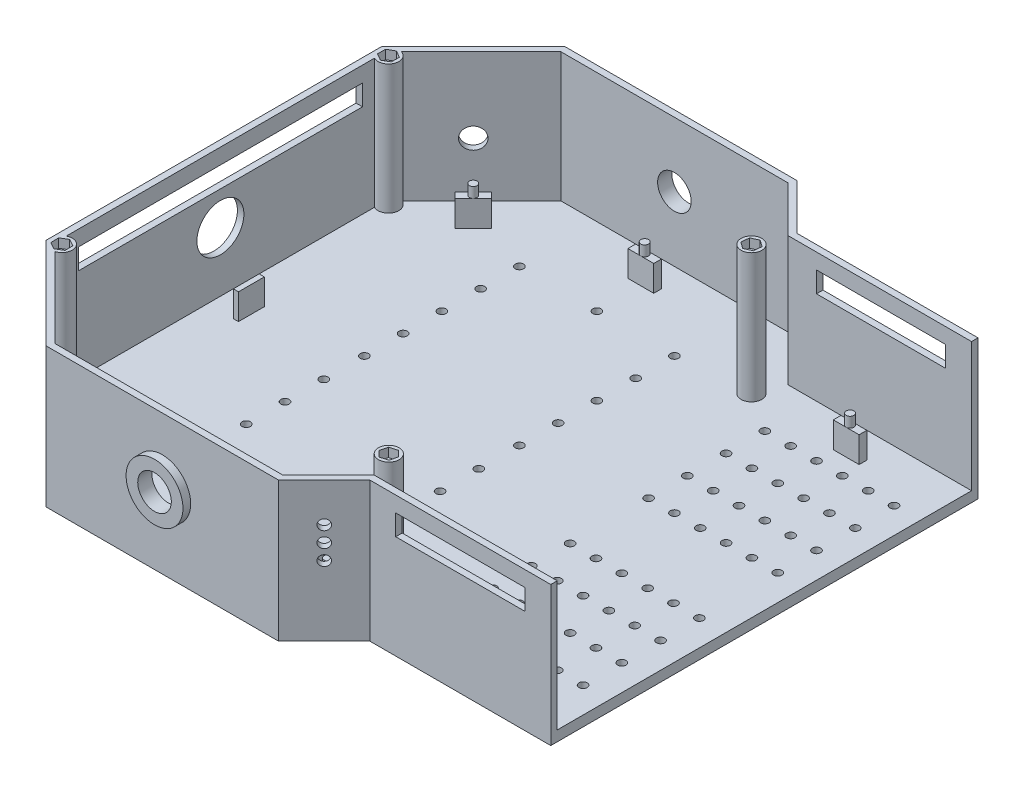
SolidWorks part; units mm, degrees
ref_plane "Ön Düzlem" through (0, 0, 0) normal (0, 0, 1) x (1, 0, 0)
ref_plane "Üst Düzlem" through (0, 0, 0) normal (0, 1, 0) x (1, 0, 0)
ref_plane "Sağ Düzlem" through (0, 0, 0) normal (1, 0, 0) x (0, 0, -1)
sketch "Çizim1" plane through (0, 0, 0) normal (0, 1, 0) x (1, 0, 0)
  line L0 (-93.9075, 105.5771) -> (-129.2628, 70.2217)
  line L1 (-129.2628, 70.2217) -> (-129.2628, -59.7783)
  line L2 (-129.2628, -59.7783) -> (-93.9075, -95.1336)
  line L3 (-93.9075, -95.1336) -> (-3.9075, -95.1336)
  line L4 (-3.9075, -95.1336) -> (13.7702, -77.4559)
  line L5 (13.7702, -77.4559) -> (83.7702, -77.4559)
  line L6 (-93.9075, 105.5771) -> (-3.9075, 105.5771)
  line L7 (-3.9075, 105.5771) -> (13.7702, 87.8994)
  line L8 (13.7702, 87.8994) -> (83.7702, 87.8994)
  line L9 (83.7702, 87.8994) -> (83.7702, -77.4559)
  dimension "D1" = 130
  dimension "D2" = 50
  dimension "D3" = 50
  dimension "D4" = 90
  dimension "D5" = 90
  dimension "D6" = 25
  dimension "D7" = 25
  dimension "D8" = 70
  dimension "D9" = 70
extrude "Yükseklik-Ekstrüzyon1" add sketch "Çizim1" along normal blind 4
ref_plane "Düzlem1" through (0, 4, 0) normal (0, 1, 0) x (1, 0, 0)
sketch "Çizim2" plane through (0, 4, 0) normal (0, 1, 0) x (1, 0, 0)
  line L0 (83.7702, 87.8994) -> (13.7702, 87.8994)
  line L2 (13.7702, 87.8994) -> (-3.9075, 105.5771)
  line L4 (-3.9075, 105.5771) -> (-93.9075, 105.5771)
  line L6 (-93.9075, 105.5771) -> (-129.2628, 70.2217)
  line L8 (-129.2628, 70.2217) -> (-129.2628, -59.7783)
  line L10 (-129.2628, -59.7783) -> (-93.9075, -95.1336)
  line L12 (-93.9075, -95.1336) -> (-3.9075, -95.1336)
  line L14 (-3.9075, -95.1336) -> (13.7702, -77.4559)
  line L16 (13.7702, -77.4559) -> (83.7702, -77.4559)
  line L18 (-126.7628, 69.1862) -> (-92.872, 103.0771)
  line L19 (-126.7628, -58.7427) -> (-126.7628, 69.1862)
  line L20 (-126.7628, -58.7427) -> (-92.872, -92.6336)
  line L21 (-92.872, -92.6336) -> (-4.943, -92.6336)
  line L22 (12.7346, -74.9559) -> (-4.943, -92.6336)
  line L23 (12.7346, -74.9559) -> (83.7702, -74.9559)
  line L24 (-4.943, 103.0771) -> (-92.872, 103.0771)
  line L25 (12.7346, 85.3994) -> (-4.943, 103.0771)
  line L26 (12.7346, 85.3994) -> (83.7702, 85.3994)
  line L27 (83.7702, -77.4559) -> (83.7702, -74.9559)
  line L28 (83.7702, 85.3994) -> (83.7702, 87.8994)
extrude "Yükseklik-Ekstrüzyon2" add sketch "Çizim2" along normal blind 50
ref_plane "Düzlem2" through (-94.5205, 0, 94.5205) normal (-0.7071, 0, 0.7071) x (0.7071, 0, 0.7071)
sketch "Çizim3" plane through (-94.5205, 0, 94.5205) normal (-0.7071, 0, 0.7071) x (0.7071, 0, 0.7071)
  circle A0 centre (-24.133, 25) radius 4.05
  dimension "D1" = 8.1
extrude "Kes-Ekstrüzyon1" cut sketch "Çizim3" against normal blind 50
ref_plane "Düzlem3" through (-99.7423, 0, -99.7423) normal (-0.7071, 0, -0.7071) x (-0.7071, 0, 0.7071)
sketch "Çizim4" plane through (-99.7423, 0, -99.7423) normal (-0.7071, 0, -0.7071) x (-0.7071, 0, 0.7071)
  circle A0 centre (16.7484, 25) radius 4.05
  dimension "D1" = 8.1
extrude "Kes-Ekstrüzyon2" cut sketch "Çizim4" against normal blind 50
ref_plane "Düzlem4" through (-129.2628, 0, 0) normal (-1, 0, 0) x (0, 0, 1)
ref_plane "Düzlem5" through (0, 0, 95.1336) normal (0, 0, 1) x (1, 0, 0)
ref_plane "Düzlem6" through (0, 4, 0) normal (0, 1, 0) x (1, 0, 0)
ref_plane "Düzlem7" through (83.7702, 0, 0) normal (1, 0, 0) x (0, 0, -1)
ref_plane "Düzlem9" through (83.7702, 0, 0) normal (1, 0, 0) x (0, 0, -1)
ref_plane "Düzlem10" through (0, 4, 0) normal (0, 1, 0) x (1, 0, 0)
sketch "Çizim7" plane through (0, 4, 0) normal (0, 1, 0) x (1, 0, 0)
  line L2 (43.2524, 75.3994) -> (53.2524, 75.3994)
  line L4 (-6.7108, 90.7027) -> (0.3603, 83.6316)
  line L5 (-1.7611, 81.5103) -> (-8.8321, 88.5814)
  line L6 (-53.9075, 93.0771) -> (-43.9075, 93.0771)
  line L7 (-8.8321, 88.5814) -> (-6.7108, 90.7027)
  line L8 (-106.2819, 75.525) -> (-99.2108, 82.5961)
  line L9 (53.2524, 75.3994) -> (53.2524, 72.3994)
  line L10 (-116.7628, 0.2217) -> (-116.7628, 10.2217)
  line L11 (53.2524, 72.3994) -> (43.2524, 72.3994)
  line L12 (-116.7628, 10.2217) -> (-114.7628, 10.2217)
  line L13 (-114.7628, 10.2217) -> (-114.7628, 0.2217)
  line L14 (-114.7628, 0.2217) -> (-116.7628, 0.2217)
  line L15 (-99.2108, 82.5961) -> (-97.0895, 80.4748)
  line L16 (-97.0895, 80.4748) -> (-104.1606, 73.4037)
  line L17 (-104.1606, 73.4037) -> (-106.2819, 75.525)
  line L18 (-43.9075, 93.0771) -> (-43.9075, 90.0771)
  line L19 (-43.9075, 90.0771) -> (-53.9075, 90.0771)
  line L20 (-53.9075, 90.0771) -> (-53.9075, 93.0771)
  line L21 (0.3603, 83.6316) -> (-1.7611, 81.5103)
  line L24 (43.2524, 72.3994) -> (43.2524, 75.3994)
  line L26 (43.2524, -61.9559) -> (43.2524, -64.9559)
  line L27 (0.3603, -73.1882) -> (-1.7611, -71.0668)
  line L28 (-53.9075, -79.6336) -> (-53.9075, -82.6336)
  line L29 (-43.9075, -79.6336) -> (-53.9075, -79.6336)
  line L30 (-43.9075, -82.6336) -> (-43.9075, -79.6336)
  line L31 (-104.1606, -62.9602) -> (-106.2819, -65.0816)
  line L32 (-97.0895, -70.0313) -> (-104.1606, -62.9602)
  line L33 (-99.2108, -72.1526) -> (-97.0895, -70.0313)
  line L34 (53.2524, -61.9559) -> (43.2524, -61.9559)
  line L35 (53.2524, -64.9559) -> (53.2524, -61.9559)
  line L36 (-106.2819, -65.0816) -> (-99.2108, -72.1526)
  line L37 (-8.8321, -78.1379) -> (-6.7108, -80.2592)
  line L38 (-53.9075, -82.6336) -> (-43.9075, -82.6336)
  line L39 (-1.7611, -71.0668) -> (-8.8321, -78.1379)
  line L40 (-6.7108, -80.2592) -> (0.3603, -73.1882)
  line L41 (43.2524, -64.9559) -> (53.2524, -64.9559)
extrude "Yükseklik-Ekstrüzyon3" add sketch "Çizim7" along normal blind 10
ref_plane "Düzlem11" through (0, 0, 95.1336) normal (0, 0, 1) x (1, 0, 0)
sketch "Çizim8" plane through (0, 0, 95.1336) normal (0, 0, 1) x (1, 0, 0)
  line L0 (-48.9075, 0) -> (-48.9075, 29)
  line L1 (-93.9075, 0) -> (-3.9075, 0) construction
  circle A0 centre (-48.9075, 29) radius 11
  dimension "D1" = 22
  dimension "D2" = 29
extrude "Yükseklik-Ekstrüzyon5" add sketch "Çizim8" along normal blind 3
ref_plane "Düzlem13" through (0, 0, -105.5771) normal (0, 0, -1) x (-1, 0, 0)
sketch "Çizim9" plane through (0, 0, -105.5771) normal (0, 0, -1) x (-1, 0, 0)
  line L0 (48.9075, 0) -> (48.9075, 29)
  line L1 (3.9075, 0) -> (93.9075, 0) construction
  circle A0 centre (48.9075, 29) radius 11
  dimension "D1" = 22
  dimension "D2" = 29
extrude "Yükseklik-Ekstrüzyon6" add sketch "Çizim9" along normal blind 3
ref_plane "Düzlem14" through (0, 0, -108.5771) normal (0, 0, -1) x (-1, 0, 0)
sketch "Çizim11" plane through (0, 0, -108.5771) normal (0, 0, -1) x (-1, 0, 0)
  circle A0 centre (48.9075, 29) radius 6.5
  dimension "D1" = 13
extrude "Kes-Ekstrüzyon4" cut sketch "Çizim11" against normal blind 232
ref_plane "Düzlem15" through (0, 4, 0) normal (0, 1, 0) x (1, 0, 0)
sketch "Çizim12" plane through (0, 4, 0) normal (0, 1, 0) x (1, 0, 0)
  line L0 (-48.9075, 103.0771) -> (-48.9075, 73.0771)
  line L1 (-92.872, 103.0771) -> (-4.943, 103.0771) construction
  line L4 (-48.9075, -92.6336) -> (-48.9075, -62.6336)
  line L5 (-4.943, -92.6336) -> (-92.872, -92.6336) construction
  circle A0 centre (-78.9075, 73.0771) radius 1.6
  circle A1 centre (-18.9075, 73.0771) radius 1.6
  circle A2 centre (-18.9075, 58.0771) radius 1.6
  circle A3 centre (-18.9075, 43.0771) radius 1.6
  circle A4 centre (-18.9075, 28.0771) radius 1.6
  circle A5 centre (-18.9075, 13.0771) radius 1.6
  circle A6 centre (-18.9075, -2.6336) radius 1.6
  circle A7 centre (-18.9075, -17.6336) radius 1.6
  circle A8 centre (-18.9075, -32.6336) radius 1.6
  circle A9 centre (-18.9075, -47.6336) radius 1.6
  circle A10 centre (-78.9075, -47.6336) radius 1.6
  circle A11 centre (-78.9075, -62.6336) radius 1.6
  circle A12 centre (-18.9075, -62.6336) radius 1.6
  circle A13 centre (-78.9075, 58.0771) radius 1.6
  circle A14 centre (-78.9075, 43.0771) radius 1.6
  circle A15 centre (-78.9075, 28.0771) radius 1.6
  circle A16 centre (-78.9075, 13.0771) radius 1.6
  circle A17 centre (-78.9075, -2.6336) radius 1.6
  circle A18 centre (-78.9075, -17.6336) radius 1.6
  circle A19 centre (-78.9075, -32.6336) radius 1.6
  circle A20 centre (-48.9075, -62.6336) radius 1.6
  circle A21 centre (-48.9075, 73.0771) radius 1.6
  dimension "D1" = 3.2
  dimension "D2" = 3.2
  dimension "D3" = 3.2
  dimension "D4" = 3.2
  dimension "D5" = 3.2
  dimension "D6" = 3.2
  dimension "D7" = 3.2
  dimension "D8" = 3.2
  dimension "D9" = 3.2
  dimension "D10" = 3.2
  dimension "D11" = 3.2
  dimension "D12" = 3.2
  dimension "D13" = 3.2
  dimension "D14" = 3.2
  dimension "D15" = 3.2
  dimension "D16" = 3.2
  dimension "D17" = 3.2
  dimension "D18" = 3.2
  dimension "D19" = 3.2
  dimension "D20" = 3.2
  dimension "D21" = 3.2
  dimension "D22" = 3.2
extrude "Kes-Ekstrüzyon5" cut sketch "Çizim12" against normal blind 10 contours A11 | A20 | A12 | A9 | A8 | A7 | A6 | A5 | A4 | A3 | A2 | A1 | A21 | A0 | A13 | A14 | A15 | A16 | A17 | A18 | A19 | A10
sketch "Çizim13" plane through (0, 4, 0) normal (0, 1, 0) x (1, 0, 0)
  line L0 (83.7702, 85.3994) -> (83.7702, 65.3994)
  line L1 (83.7702, -74.9559) -> (83.7702, 85.3994) construction
  line L3 (83.7702, -74.9559) -> (83.7702, -54.9559)
  circle A0 centre (73.7702, 65.3994) radius 1.6
  circle A1 centre (63.7702, 65.3994) radius 1.6
  circle A2 centre (53.7702, 65.3994) radius 1.6
  circle A3 centre (43.7702, 65.3994) radius 1.6
  circle A4 centre (33.7702, 65.3994) radius 1.6
  circle A5 centre (23.7702, 65.3994) radius 1.6
  circle A6 centre (23.7702, 50.3994) radius 1.6
  circle A7 centre (33.7702, 50.3994) radius 1.6
  circle A8 centre (43.7702, 50.3994) radius 1.6
  circle A9 centre (53.7702, 50.3994) radius 1.6
  circle A10 centre (63.7702, 50.3994) radius 1.6
  circle A11 centre (73.7702, 50.3994) radius 1.6
  circle A12 centre (53.7702, 35.3994) radius 1.6
  circle A13 centre (63.7702, 35.3994) radius 1.6
  circle A14 centre (73.7702, 35.3994) radius 1.6
  circle A15 centre (73.7702, 20.3994) radius 1.6
  circle A16 centre (63.7702, 20.3994) radius 1.6
  circle A17 centre (53.7702, 20.3994) radius 1.6
  circle A18 centre (43.7702, 20.3994) radius 1.6
  circle A19 centre (43.7702, 35.3994) radius 1.6
  circle A20 centre (33.7702, 35.3994) radius 1.6
  circle A21 centre (33.7702, 20.3994) radius 1.6
  circle A22 centre (23.7702, 20.3994) radius 1.6
  circle A23 centre (23.7702, 35.3994) radius 1.6
  circle A24 centre (23.7702, -24.9559) radius 1.6
  circle A25 centre (23.7702, -9.9559) radius 1.6
  circle A26 centre (33.7702, -9.9559) radius 1.6
  circle A27 centre (33.7702, -24.9559) radius 1.6
  circle A28 centre (43.7702, -24.9559) radius 1.6
  circle A29 centre (43.7702, -9.9559) radius 1.6
  circle A30 centre (53.7702, -9.9559) radius 1.6
  circle A31 centre (63.7702, -9.9559) radius 1.6
  circle A32 centre (73.7702, -9.9559) radius 1.6
  circle A33 centre (73.7702, -24.9559) radius 1.6
  circle A34 centre (63.7702, -24.9559) radius 1.6
  circle A35 centre (53.7702, -24.9559) radius 1.6
  circle A36 centre (73.7702, -39.9559) radius 1.6
  circle A37 centre (63.7702, -39.9559) radius 1.6
  circle A38 centre (53.7702, -39.9559) radius 1.6
  circle A39 centre (43.7702, -39.9559) radius 1.6
  circle A40 centre (33.7702, -39.9559) radius 1.6
  circle A41 centre (23.7702, -39.9559) radius 1.6
  circle A42 centre (23.7702, -54.9559) radius 1.6
  circle A43 centre (33.7702, -54.9559) radius 1.6
  circle A44 centre (43.7702, -54.9559) radius 1.6
  circle A45 centre (53.7702, -54.9559) radius 1.6
  circle A46 centre (63.7702, -54.9559) radius 1.6
  circle A47 centre (73.7702, -54.9559) radius 1.6
extrude "Kes-Ekstrüzyon6" cut sketch "Çizim13" against normal blind 10 contours A42 | A43 | A44 | A45 | A46 | A47 | A36 | A37 | A38 | A39 | A40 | A41 | A24 | A27 | A28 | A35 | A34 | A33 | A32 | A31 | A30 | A29 | A26 | A25 | A22 | A21 | A18 | A17 | A16 | A15 | A14 | A11 | A0 | A1 | A10 | A13 | A12 | A9 | A2 | A3 | A8 | A19 | A20 | A23 | A6 | A7 | A4 | A5
ref_plane "Düzlem16" through (-129.2628, 0, 0) normal (-1, 0, 0) x (0, 0, 1)
sketch "Çizim14" plane through (-129.2628, 0, 0) normal (-1, 0, 0) x (0, 0, 1)
  line L21 (-60.2217, 44) -> (-60.2217, 48)
  line L22 (59.7783, 44) -> (49.7783, 44)
  line L23 (59.7783, 54) -> (59.7783, 0) construction
  line L24 (49.7783, 44) -> (49.7783, 48)
  line L25 (49.7783, 48) -> (-60.2217, 48)
  line L26 (-60.2217, 44) -> (-60.2217, 40)
  line L27 (-60.2217, 40) -> (49.7783, 40)
  line L28 (49.7783, 40) -> (49.7783, 44)
  circle A1 centre (-5.2217, 27) radius 9.1
  dimension "D1" = 18.2
extrude "Kes-Ekstrüzyon7" cut sketch "Çizim14" against normal blind 10 contours L27 L28 L24 L25 L21 L26 | A1
ref_plane "Düzlem17" through (0, 0, 77.4559) normal (0, 0, 1) x (1, 0, 0)
sketch "Çizim15" plane through (0, 0, 77.4559) normal (0, 0, 1) x (1, 0, 0)
  line L8 (73.7702, 48) -> (23.7702, 48)
  line L9 (23.7702, 48) -> (23.7702, 40)
  line L10 (23.7702, 40) -> (73.7702, 40)
  line L11 (73.7702, 40) -> (73.7702, 48)
extrude "Kes-Ekstrüzyon8" cut sketch "Çizim15" against normal blind 190
ref_plane "Düzlem18" through (0, 4, 0) normal (0, 1, 0) x (1, 0, 0)
sketch "Çizim16" plane through (0, 4, 0) normal (0, 1, 0) x (1, 0, 0)
  circle A2 centre (8.5925, 75.3994) radius 4
  circle A3 centre (-124.9151, 68.4208) radius 4
  circle A4 centre (-124.9151, -57.9774) radius 4
  circle A5 centre (8.5925, -64.9559) radius 4
  dimension "D1" = 8
  dimension "D2" = 8
  dimension "D3" = 8
  dimension "D4" = 8
extrude "Yükseklik-Ekstrüzyon7" add sketch "Çizim16" along normal up to surface (50 mm away) up to face at (-25.7611, 54, -5.2217)
ref_plane "Düzlem19" through (0, 54, 0) normal (0, 1, 0) x (1, 0, 0)
sketch "Çizim17" plane through (0, 54, 0) normal (0, 1, 0) x (1, 0, 0)
  circle A0 centre (-124.9151, 68.4208) radius 1.6
  circle A1 centre (-124.9151, -57.9774) radius 1.6
  circle A2 centre (8.5925, 75.3994) radius 1.6
  circle A3 centre (8.5925, -64.9559) radius 1.6
  dimension "D1" = 3.2
  dimension "D2" = 3.2
  dimension "D3" = 3.2
  dimension "D4" = 3.2
extrude "Kes-Ekstrüzyon9" cut sketch "Çizim17" against normal blind 190
sketch "Çizim18" plane through (0, 54, 0) normal (0, 1, 0) x (1, 0, 0)
  line L1 (-122.2397, 66.8548) -> (-122.2212, 69.9548)
  line L2 (-122.2212, 69.9548) -> (-124.8965, 71.5208)
  line L3 (-124.8965, 71.5208) -> (-127.5904, 69.9869)
  line L4 (-127.5904, 69.9869) -> (-127.609, 66.8869)
  line L5 (-127.609, 66.8869) -> (-124.9336, 65.3209)
  line L6 (-124.9336, 65.3209) -> (-122.2397, 66.8548)
  line L7 (-122.1984, -59.4705) -> (-122.2636, -56.3712)
  line L8 (-122.2636, -56.3712) -> (-124.9803, -54.878)
  line L9 (-124.9803, -54.878) -> (-127.6318, -56.4842)
  line L10 (-127.6318, -56.4842) -> (-127.5665, -59.5835)
  line L11 (-127.5665, -59.5835) -> (-124.8498, -61.0767)
  line L12 (-124.8498, -61.0767) -> (-122.1984, -59.4705)
  line L13 (10.8202, -67.1117) -> (11.5733, -64.1046)
  line L14 (11.5733, -64.1046) -> (9.3456, -61.9488)
  line L15 (9.3456, -61.9488) -> (6.3648, -62.8001)
  line L16 (6.3648, -62.8001) -> (5.6117, -65.8073)
  line L17 (5.6117, -65.8073) -> (7.8394, -67.9631)
  line L18 (7.8394, -67.9631) -> (10.8202, -67.1117)
  line L19 (11.1104, 73.591) -> (11.4176, 76.6757)
  line L20 (11.4176, 76.6757) -> (8.8997, 78.4842)
  line L21 (8.8997, 78.4842) -> (6.0746, 77.2078)
  line L22 (6.0746, 77.2078) -> (5.7674, 74.1231)
  line L23 (5.7674, 74.1231) -> (8.2853, 72.3147)
  line L24 (8.2853, 72.3147) -> (11.1104, 73.591)
  circle A0 centre (-124.9151, 68.4208) radius 2.6847 construction
  circle A1 centre (-124.9151, -57.9774) radius 2.6847 construction
  circle A2 centre (8.5925, -64.9559) radius 2.6847 construction
  circle A3 centre (8.5925, 75.3994) radius 2.6847 construction
  dimension "D1" = 6.2
  dimension "D2" = 6.2
  dimension "D3" = 6.2
  dimension "D4" = 6.2
extrude "Kes-Ekstrüzyon10" cut sketch "Çizim18" against normal blind 3.5
sketch "Çizim19" plane through (0, 4, 0) normal (0, 1, 0) x (1, 0, 0)
  circle A0 centre (-101.6857, 77.9999) radius 1.5
  circle A2 centre (-101.6857, -67.5564) radius 1.5
  circle A3 centre (-48.9075, -81.1336) radius 1.5
  circle A4 centre (-4.2359, -75.663) radius 1.5
  circle A5 centre (48.2524, -63.4559) radius 1.5
  circle A6 centre (-48.9075, 91.5771) radius 1.5
  circle A7 centre (-4.2359, 86.1065) radius 1.5
  circle A8 centre (48.2524, 73.8994) radius 1.5
  dimension "D1" = 3
extrude "Yükseklik-Ekstrüzyon8" add sketch "Çizim19" along normal blind 14
ref_plane "Düzlem20" through (45.613, 0, 45.613) normal (0.7071, 0, 0.7071) x (0.7071, 0, -0.7071)
sketch "Çizim20" plane through (45.613, 0, 45.613) normal (0.7071, 0, 0.7071) x (0.7071, 0, -0.7071)
  circle A0 centre (-57.5326, 39) radius 2
  circle A1 centre (-57.5326, 33) radius 2
  circle A2 centre (-57.5326, 27) radius 2
  dimension "D5" = 4
  dimension "D6" = 4
  dimension "D7" = 4
  dimension "D2" = 6
  dimension "D3" = 6
extrude "Kes-Ekstrüzyon11" cut sketch "Çizim20" against normal blind 14
ref_plane "Düzlem21" through (50.8348, 0, -50.8348) normal (0.7071, 0, -0.7071) x (-0.7071, 0, -0.7071)
sketch "Çizim21" plane through (50.8348, 0, -50.8348) normal (0.7071, 0, -0.7071) x (-0.7071, 0, -0.7071)
  circle A0 centre (64.9173, 39) radius 2
  circle A1 centre (64.9173, 33) radius 2
  circle A2 centre (64.9173, 27) radius 2
  dimension "D4" = 4
  dimension "D5" = 4
  dimension "D6" = 4
  dimension "D2" = 6
  dimension "D3" = 6
extrude "Kes-Ekstrüzyon12" cut sketch "Çizim21" against normal blind 14
